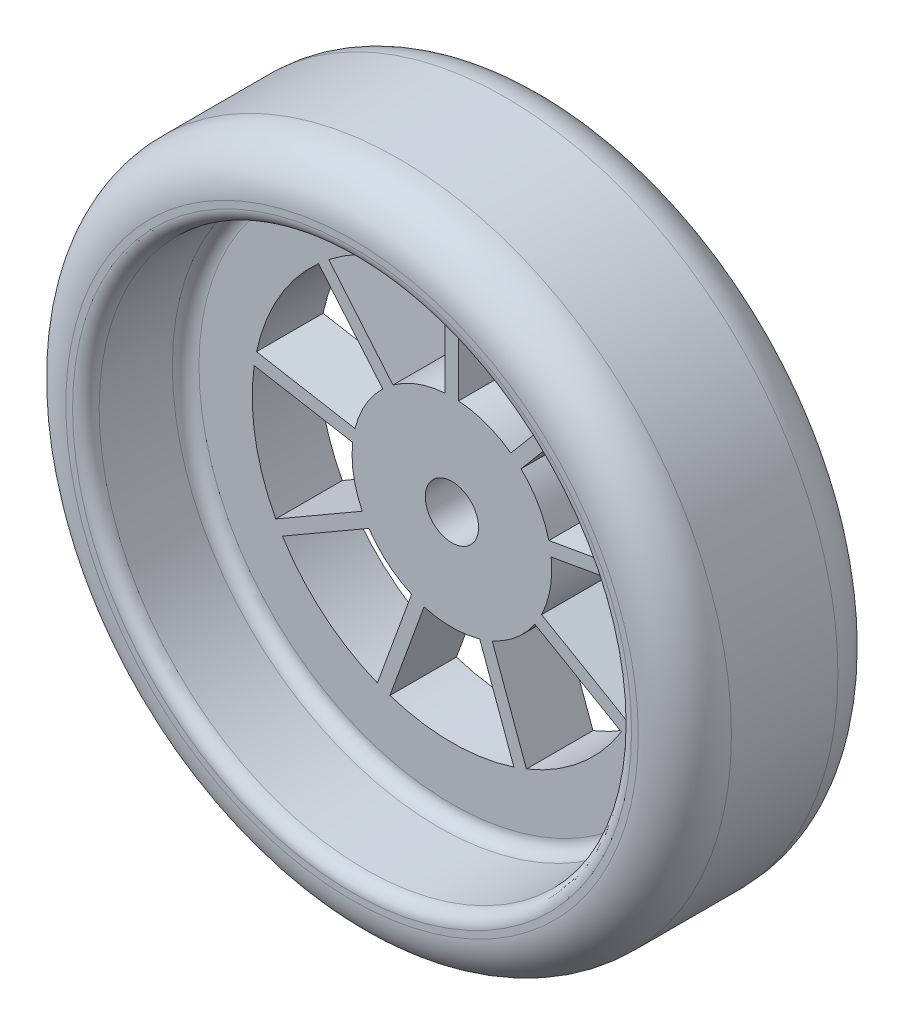
SolidWorks part; units mm, degrees
ref_plane "Front Plane" through (0, 0, 0) normal (0, 0, 1) x (1, 0, 0)
ref_plane "Top Plane" through (0, 0, 0) normal (0, 1, 0) x (1, 0, 0)
ref_plane "Right Plane" through (0, 0, 0) normal (1, 0, 0) x (0, 0, -1)
sketch "Sketch1" plane through (0, 0, 0) normal (0, 0, 1) x (1, 0, 0)
  circle A0 centre (0, 0) radius 50
  circle A1 centre (0, 0) radius 40
  dimension "D1" = 100
  dimension "D2" = 80
extrude "Boss-Extrude1" add sketch "Sketch1" along normal blind 30
fillet "Fillet1" radius 7 2 edges at (50, 0, 0) (50, 0, 30)
sketch "Sketch3" plane through (0, 0, 0) normal (0, 0, 1) x (1, 0, 0)
  line L0 (-1, 14.9666) -> (-1, 29.9833)
  line L1 (1, 14.9666) -> (1, 29.9833)
  line L4 (8.8543, 12.1079) -> (18.5069, 23.6113)
  line L5 (10.3864, 10.8223) -> (20.039, 22.3258)
  line L6 (14.5656, 3.5837) -> (29.3542, 6.1914)
  line L7 (14.9129, 1.6141) -> (29.7015, 4.2217)
  line L8 (13.4615, -6.6173) -> (26.4663, -14.1256)
  line L9 (12.4615, -8.3493) -> (25.4663, -15.8577)
  line L10 (6.0586, -13.722) -> (11.1946, -27.8331)
  line L11 (4.1792, -14.4061) -> (9.3152, -28.5171)
  line L12 (-4.1792, -14.4061) -> (-9.3152, -28.5171)
  line L13 (-6.0586, -13.722) -> (-11.1946, -27.8331)
  line L14 (-12.4615, -8.3493) -> (-25.4663, -15.8577)
  line L15 (-13.4615, -6.6173) -> (-26.4663, -14.1256)
  line L16 (-14.9129, 1.6141) -> (-29.7015, 4.2217)
  line L17 (-14.5656, 3.5837) -> (-29.3542, 6.1914)
  line L18 (-10.3864, 10.8223) -> (-20.039, 22.3258)
  line L19 (-8.8543, 12.1079) -> (-18.5069, 23.6113)
  arc A0 (5.1303, 14.0954) -> (1, 14.9666) centre (0, 0) ccw
  circle A1 centre (0, 0) radius 40
  arc A2 (-18.5069, 23.6113) -> (-20.039, 22.3258) centre (0, 0) ccw
  arc A3 (-1, 14.9666) -> (-5.1303, 14.0954) centre (0, 0) ccw
  arc A4 (12.9904, 7.5) -> (10.3864, 10.8223) centre (0, 0) ccw
  arc A5 (8.8543, 12.1079) -> (5.1303, 14.0954) centre (0, 0) ccw
  arc A6 (14.7721, -2.6047) -> (14.9129, 1.6141) centre (0, 0) ccw
  arc A7 (14.5656, 3.5837) -> (12.9904, 7.5) centre (0, 0) ccw
  arc A8 (9.6418, -11.4907) -> (12.4615, -8.3493) centre (0, 0) ccw
  arc A9 (13.4615, -6.6173) -> (14.7721, -2.6047) centre (0, 0) ccw
  arc A10 (0, -15) -> (4.1792, -14.4061) centre (0, 0) ccw
  arc A11 (6.0586, -13.722) -> (9.6418, -11.4907) centre (0, 0) ccw
  arc A12 (-9.6418, -11.4907) -> (-6.0586, -13.722) centre (0, 0) ccw
  arc A13 (-4.1792, -14.4061) -> (0, -15) centre (0, 0) ccw
  arc A14 (-14.7721, -2.6047) -> (-13.4615, -6.6173) centre (0, 0) ccw
  arc A15 (-12.4615, -8.3493) -> (-9.6418, -11.4907) centre (0, 0) ccw
  arc A16 (-12.9904, 7.5) -> (-14.5656, 3.5837) centre (0, 0) ccw
  arc A17 (-14.9129, 1.6141) -> (-14.7721, -2.6047) centre (0, 0) ccw
  arc A18 (-5.1303, 14.0954) -> (-8.8543, 12.1079) centre (0, 0) ccw
  arc A19 (-10.3864, 10.8223) -> (-12.9904, 7.5) centre (0, 0) ccw
  arc A20 (-29.3542, 6.1914) -> (-29.7015, 4.2217) centre (0, 0) ccw
  arc A21 (-26.4663, -14.1256) -> (-25.4663, -15.8577) centre (0, 0) ccw
  arc A22 (-11.1946, -27.8331) -> (-9.3152, -28.5171) centre (0, 0) ccw
  arc A23 (9.3152, -28.5171) -> (11.1946, -27.8331) centre (0, 0) ccw
  arc A24 (25.4663, -15.8577) -> (26.4663, -14.1256) centre (0, 0) ccw
  arc A25 (29.7015, 4.2217) -> (29.3542, 6.1914) centre (0, 0) ccw
  arc A26 (20.039, 22.3258) -> (18.5069, 23.6113) centre (0, 0) ccw
  arc A27 (1, 29.9833) -> (-1, 29.9833) centre (0, 0) ccw
  dimension "D1" = 30
  dimension "D2" = 60
  dimension "D3" = 1
  dimension "D4" = 1
  dimension "D7" = 9
extrude "Boss-Extrude2" add sketch "Sketch3" along normal blind 10 from offset 5 separate body contours L5 A26 L4 A5 A0 L1 A27 L0 A3 A18 L19 A2 L18 A19 A16 L17 A20 L16 A17 A14 L15 A21 L14 A15 A12 L13 A22 L12 A13 A10 L11 A23 L10 A11 A8 L9 A24 L8 A9 A6 L7 A25 L6 A7 A4
sketch "Sketch4" plane through (0, 0, 15) normal (0, 0, 1) x (1, 0, 0)
  circle A0 centre (0, 0) radius 30
  circle A1 centre (0, 0) radius 40
  dimension "D1" = 80
extrude "Boss-Extrude3" add sketch "Sketch4" against normal blind 10
fillet "Fillet2" radius 2 4 edges at (40, 0, 30) (40, 0, 0) (40, 0, 5) (40, 0, 15)
sketch "Sketch5" plane through (0, 0, 15) normal (0, 0, 1) x (1, 0, 0)
  circle A0 centre (0, 0) radius 4
  dimension "D1" = 8
extrude "Cut-Extrude1" cut sketch "Sketch5" against normal blind 10
